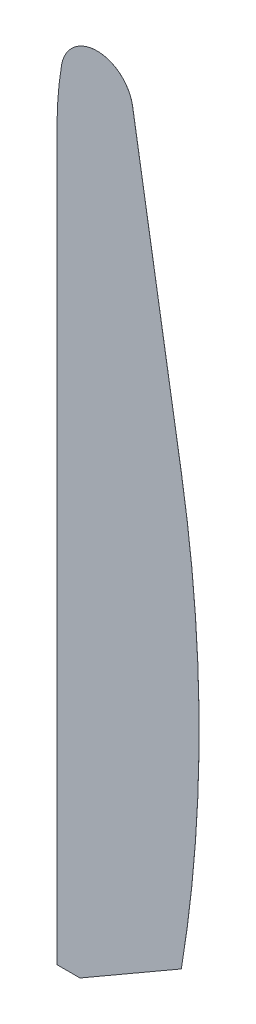
SolidWorks part; units mm, degrees
ref_plane "Front Plane" through (0, 0, 0) normal (1, 0, 0) x (0, 1, 0)
ref_plane "Top Plane" through (0, 0, 0) normal (0, 0, 1) x (0, 1, 0)
ref_plane "Right Plane" through (0, 0, 0) normal (0, 1, 0) x (-1, 0, 0)
sketch "Sketch1" plane through (0, 0, 0) normal (0, 0, 1) x (0, 1, 0)
  line L0 (0, 0) -> (0, 50000) construction
  line L1 (0, 0) -> (50000, 0) construction
  line L2 (143.5634, 601.065) -> (1381.2364, 932.6984) construction
  line L3 (0, 0) -> (158.1, 0)
  line L4 (0, 0) -> (0, -5)
  line L5 (0, -5) -> (12.7279, -27.0455)
  line L6 (170, -16.4378) -> (106.2481, -27.0455)
  line L7 (0, 0) -> (59.488, -30.9091)
  line L8 (0, 0) -> (170, -16.4378)
  arc A0 (158.1, 0) -> (170, -0.9833) centre (158.1, -72.5022) cw
  arc A1 (170, -0.9833) -> (170, -16.4378) centre (168.7143, -8.7105) cw
  arc A2 (12.7279, -27.0455) -> (106.2481, -27.0455) centre (59.488, 253.9822) ccw
  dimension "D1" = 5
  dimension "D2" = 27.0455
  dimension "D3" = 158.1
  dimension "Span" = 170
  dimension "Chord" = 30.9091
  dimension "D4" = 30
  dimension "D5" = 15.4545
extrude "Boss-Extrude1" add sketch "Sketch1" along normal blind 0.01 contours L6 A2 L5 L4 L3 A0 A1
equation "\"D3@Sketch1\"=\"Span@Sketch1\"*0.93"
equation "\"D2@Sketch1\"=\"Chord@Sketch1\"*0.875"
equation "\"Chord@Sketch1\"=\"Span@Sketch1\"/5.5"
equation "\"D5@Sketch1\"=\"Chord@Sketch1\"/2"
